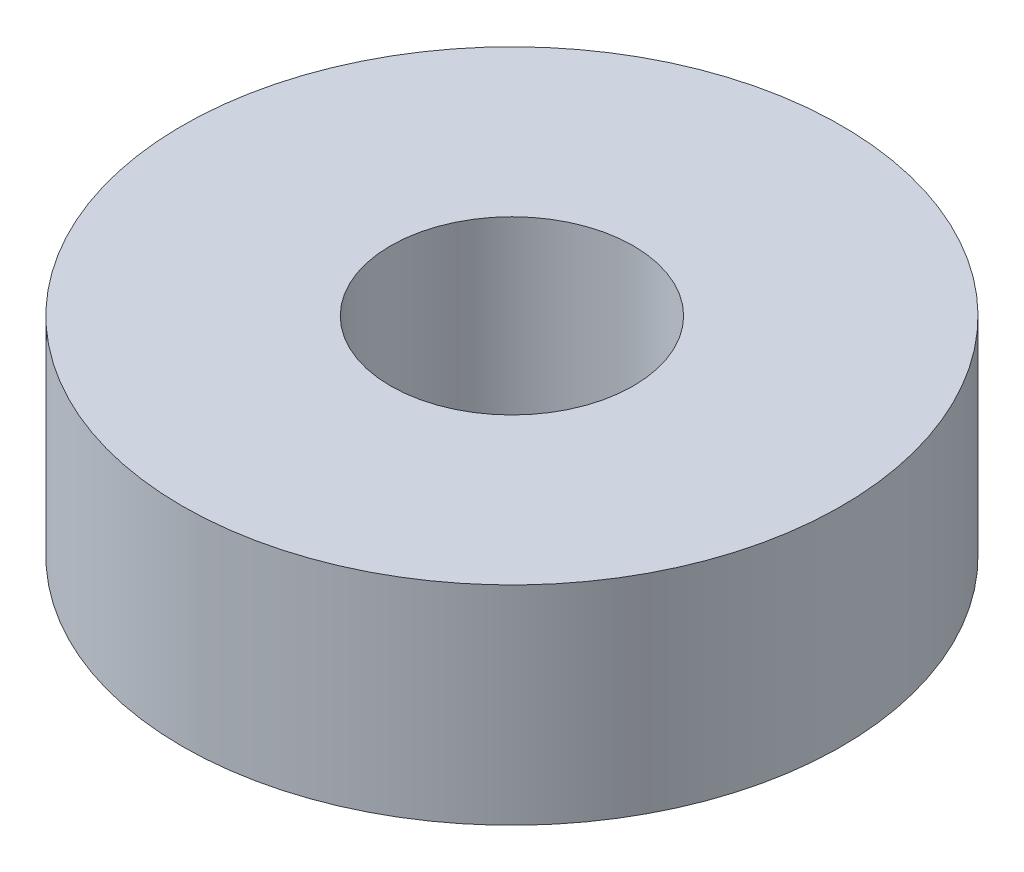
SolidWorks part; units mm, degrees
ref_plane "Front Plane" through (0, 0, 0) normal (0, 0, 1) x (1, 0, 0)
ref_plane "Top Plane" through (0, 0, 0) normal (0, 1, 0) x (1, 0, 0)
ref_plane "Right Plane" through (0, 0, 0) normal (1, 0, 0) x (0, 0, -1)
sketch "Sketch1" plane through (0, 0, 0) normal (0, 1, 0) x (1, 0, 0)
  circle A0 centre (0, 0) radius 9.5
  circle A1 centre (0, 0) radius 3.5
  dimension "D1" = 7
  dimension "D2" = 19
extrude "Boss-Extrude1" add sketch "Sketch1" along normal blind 6
